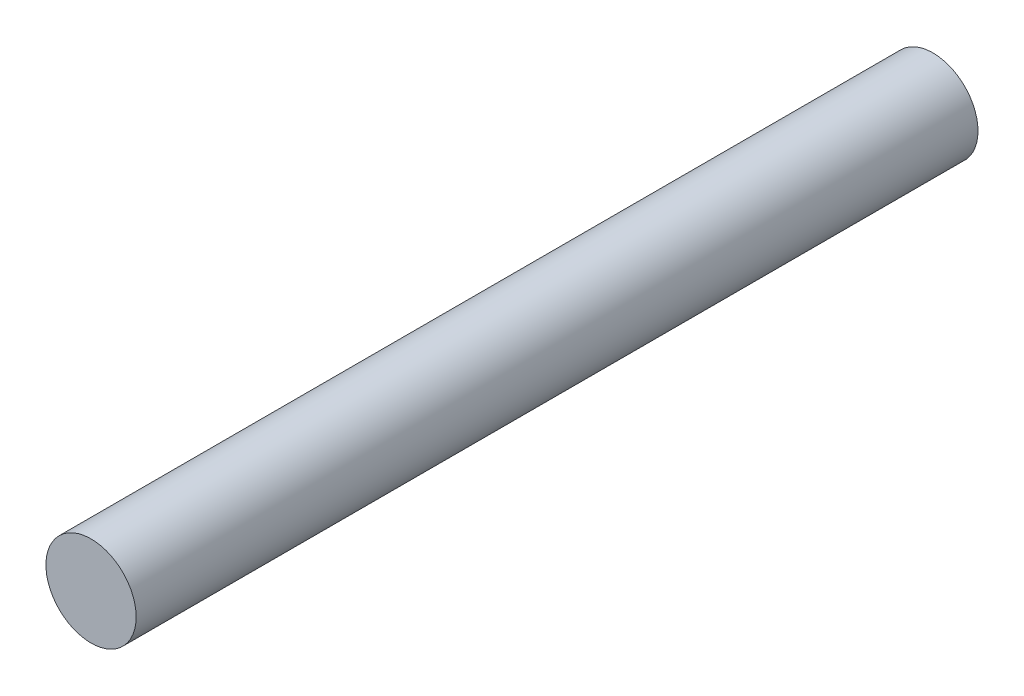
SolidWorks part; units mm, degrees
ref_plane "Front Plane" through (0, 0, 0) normal (0, 0, 1) x (1, 0, 0)
ref_plane "Top Plane" through (0, 0, 0) normal (0, 1, 0) x (1, 0, 0)
ref_plane "Right Plane" through (0, 0, 0) normal (1, 0, 0) x (0, 0, -1)
sketch "Sketch1" plane through (0, 0, 0) normal (0, 0, 1) x (1, 0, 0)
  circle A0 centre (0, 0) radius 10.72
extrude "Boss-Extrude1" add sketch "Sketch1" along normal blind 200
